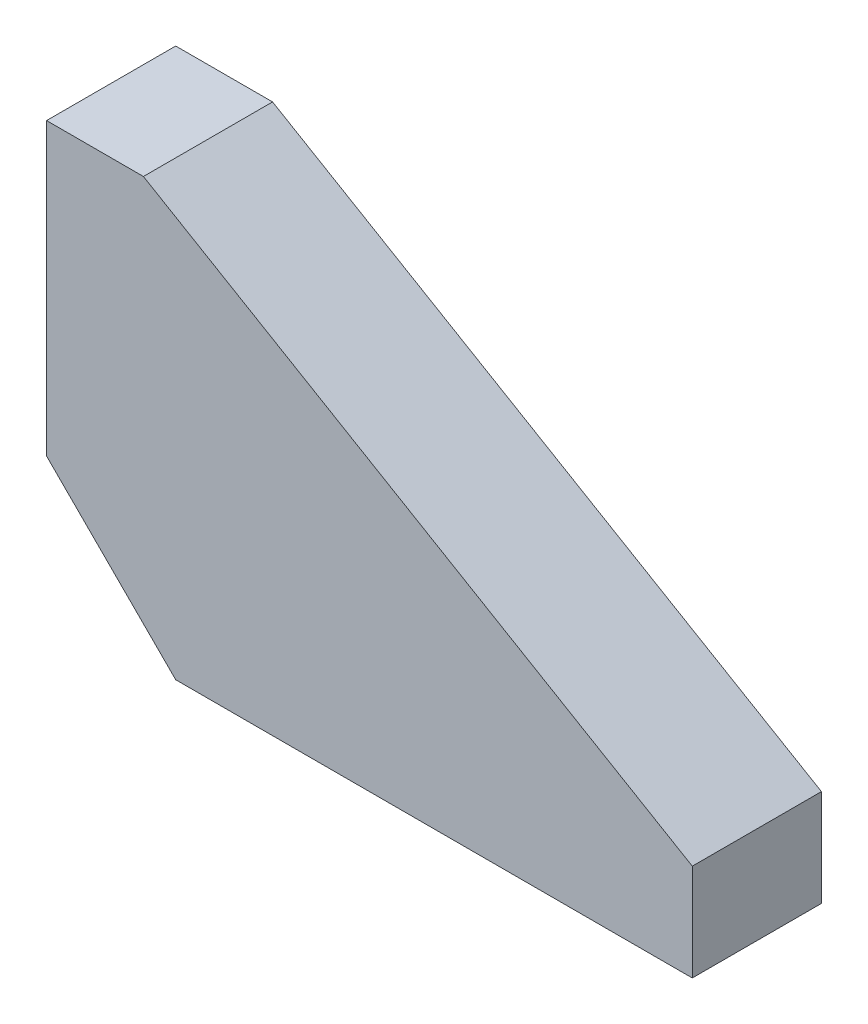
SolidWorks part; units mm, degrees
ref_plane "前视基准面" through (0, 0, 0) normal (0, 0, 1) x (1, 0, 0)
ref_plane "上视基准面" through (0, 0, 0) normal (0, 1, 0) x (1, 0, 0)
ref_plane "右视基准面" through (0, 0, 0) normal (1, 0, 0) x (0, 0, -1)
sketch "草图1" plane through (0, 0, 0) normal (0, 0, 1) x (1, 0, 0)
  line L0 (0, 0) -> (15, 0)
  line L1 (15, 0) -> (100, -50)
  line L2 (100, -50) -> (100, -65)
  line L3 (100, -65) -> (20, -65)
  line L4 (20, -65) -> (0, -45)
  line L5 (0, -45) -> (0, 0)
  dimension "D1" = 15
  dimension "D2" = 65
  dimension "D3" = 100
  dimension "D4" = 15
  dimension "D5" = 45
  dimension "D6" = 80
extrude "凸台-拉伸1" add sketch "草图1" along normal blind 20
